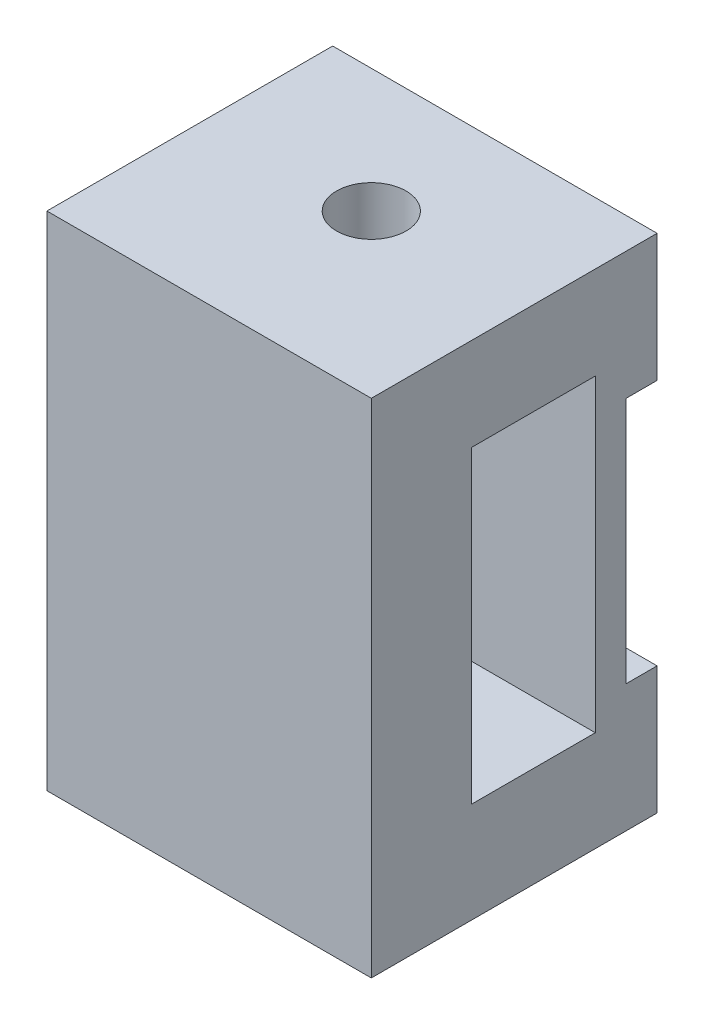
SolidWorks part; units mm, degrees
ref_plane "Plan de face" through (0, 0, 0) normal (0, 0, 1) x (1, 0, 0)
ref_plane "Plan de dessus" through (0, 0, 0) normal (0, 1, 0) x (1, 0, 0)
ref_plane "Plan de droite" through (0, 0, 0) normal (1, 0, 0) x (0, 0, -1)
sketch "Esquisse1" plane through (0, 0, 0) normal (0, 1, 0) x (1, 0, 0)
  line L1 (-21, 21) -> (21, 21)
  line L2 (-21, 21) -> (-21, -21)
  line L3 (-21, -21) -> (21, -21)
  line L4 (21, 21) -> (21, -21)
  line L5 (-21, 21) -> (21, -21) construction
  line L6 (-21, -21) -> (21, 21) construction
  point P0 (0, 0)
  dimension "D1" = 42
  dimension "D2" = 42
extrude "Boss.-Extru.6" add sketch "Esquisse1" along normal blind 12
sketch "Esquisse9" plane through (0, 0, 0) normal (0, -1, 0) x (1, 0, 0)
  line L0 (21, 21) -> (21, -21) construction
  line L1 (-21, -21) -> (21, -21)
  line L2 (-21, -21) -> (-21, -8)
  line L3 (-21, -8) -> (21, -8)
  line L4 (21, -21) -> (21, -8)
  line L6 (-21, 21) -> (21, 21)
  line L7 (-21, 21) -> (-21, 8)
  line L8 (-21, 8) -> (21, 8)
  line L9 (21, 21) -> (21, 8)
  dimension "D1" = 13
  dimension "D2" = 13
extrude "Boss.-Extru.7" add sketch "Esquisse9" along normal blind 40
sketch "Esquisse10" plane through (0, -40, 0) normal (0, -1, 0) x (1, 0, 0)
  line L1 (-21, 21) -> (21, 21)
  line L2 (-21, 21) -> (-21, -21)
  line L3 (-21, -21) -> (21, -21)
  line L4 (21, 21) -> (21, -21)
extrude "Boss.-Extru.8" add sketch "Esquisse10" along normal blind 13
sketch "Esquisse12" plane through (0, 12, 0) normal (0, 1, 0) x (1, 0, 0)
  circle A0 centre (0, 0) radius 4.5
  dimension "D1" = 9
extrude "Enlèv. mat.-Extru.3" cut sketch "Esquisse12" against normal through all
sketch "Esquisse13" plane through (0, 12, 0) normal (0, 1, 0) x (1, 0, 0)
  line L0 (21, -21) -> (21, 21) construction
  line L1 (-21, 21) -> (21, 21)
  line L2 (-21, 21) -> (-21, 16)
  line L3 (-21, 16) -> (21, 16)
  line L4 (21, 21) -> (21, 16)
  dimension "D1" = 5
extrude "Enlèv. mat.-Extru.4" cut sketch "Esquisse13" against normal through all
sketch "Esquisse15" plane through (21, 0, 0) normal (1, 0, 0) x (0, 0, -1)
  line L0 (16, -36.5) -> (16, -4.5)
  line L3 (16, -53) -> (16, 12) construction
  line L6 (16, -36.5) -> (12, -36.5)
  line L7 (16, -36.5) -> (16, -4.5)
  line L8 (16, -4.5) -> (12, -4.5)
  line L9 (12, -36.5) -> (12, -4.5)
  point P5 (16, -20.5)
  dimension "D1" = 32
  dimension "D2" = 4
extrude "Enlèv. mat.-Extru.5" cut sketch "Esquisse15" against normal through all contours L7 L6 L9 L8
